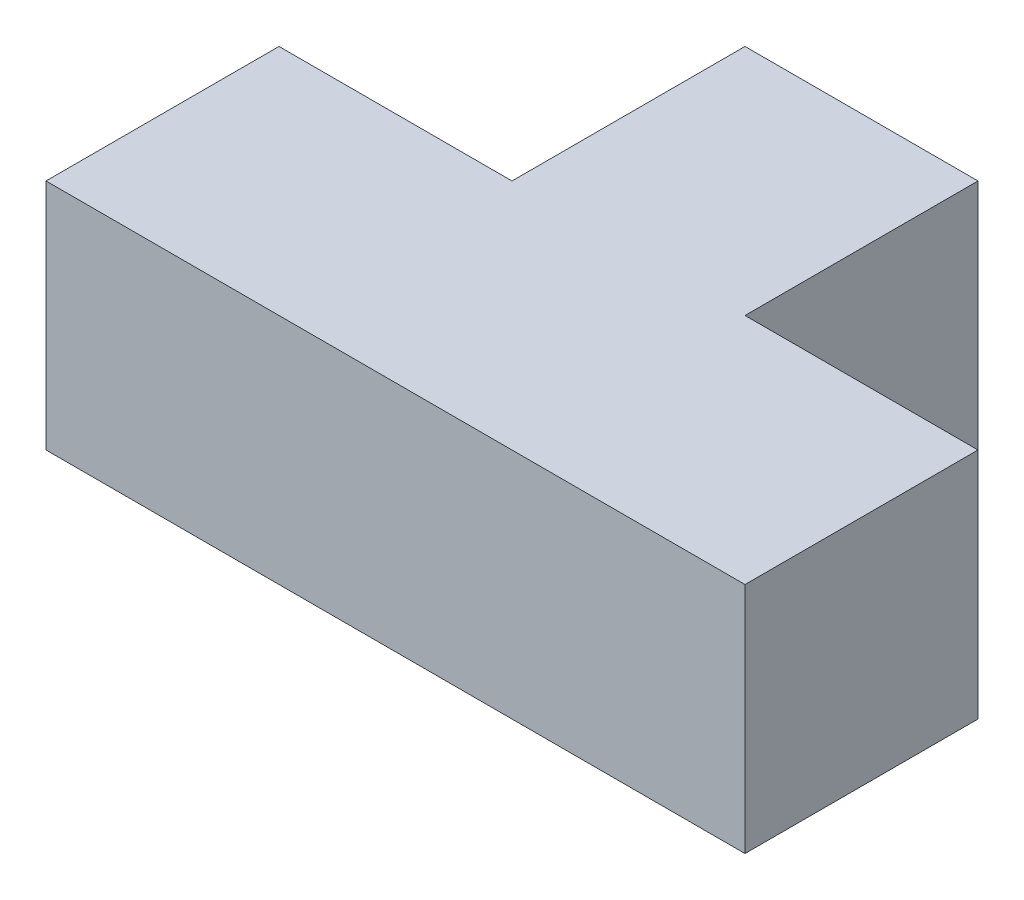
SolidWorks part; units mm, degrees
ref_plane "前基準面" through (0, 0, 0) normal (0, 0, 1) x (1, 0, 0)
ref_plane "上基準面" through (0, 0, 0) normal (0, 1, 0) x (1, 0, 0)
ref_plane "右基準面" through (0, 0, 0) normal (1, 0, 0) x (0, 0, -1)
sketch "草圖1" plane through (0, 0, 0) normal (0, 1, 0) x (1, 0, 0)
  line L1 (0, 0) -> (60, 0)
  line L2 (0, 0) -> (0, 30)
  line L3 (0, 30) -> (60, 30)
  line L4 (60, 0) -> (60, 30)
  line L5 (0, 30) -> (30, 30)
  line L6 (0, 30) -> (0, 60)
  line L7 (0, 60) -> (30, 60)
  line L8 (30, 30) -> (30, 60)
  dimension "D1" = 30
  dimension "D2" = 60
  dimension "D3" = 30
  dimension "D4" = 30
extrude "填料-伸長1" add sketch "草圖1" along normal blind 30 contours L1 L4 L3 L2 | L3 L8 L7 L6
sketch "草圖2" plane through (0, 0, 0) normal (-1, 0, 0) x (0, 0, 1)
  line L4 (-30, 0) -> (0, 0)
  line L5 (-30, 30) -> (-30, 0)
  line L6 (0, 30) -> (-30, 30)
  line L7 (0, 0) -> (0, 30)
  line L8 (-30, 0) -> (0, 0)
  line L9 (-30, 30) -> (-30, 0)
  line L10 (0, 30) -> (-30, 30)
  line L11 (0, 0) -> (0, 30)
  dimension "D1" = 0
extrude "填料-伸長2" add sketch "草圖2" along normal blind 30
